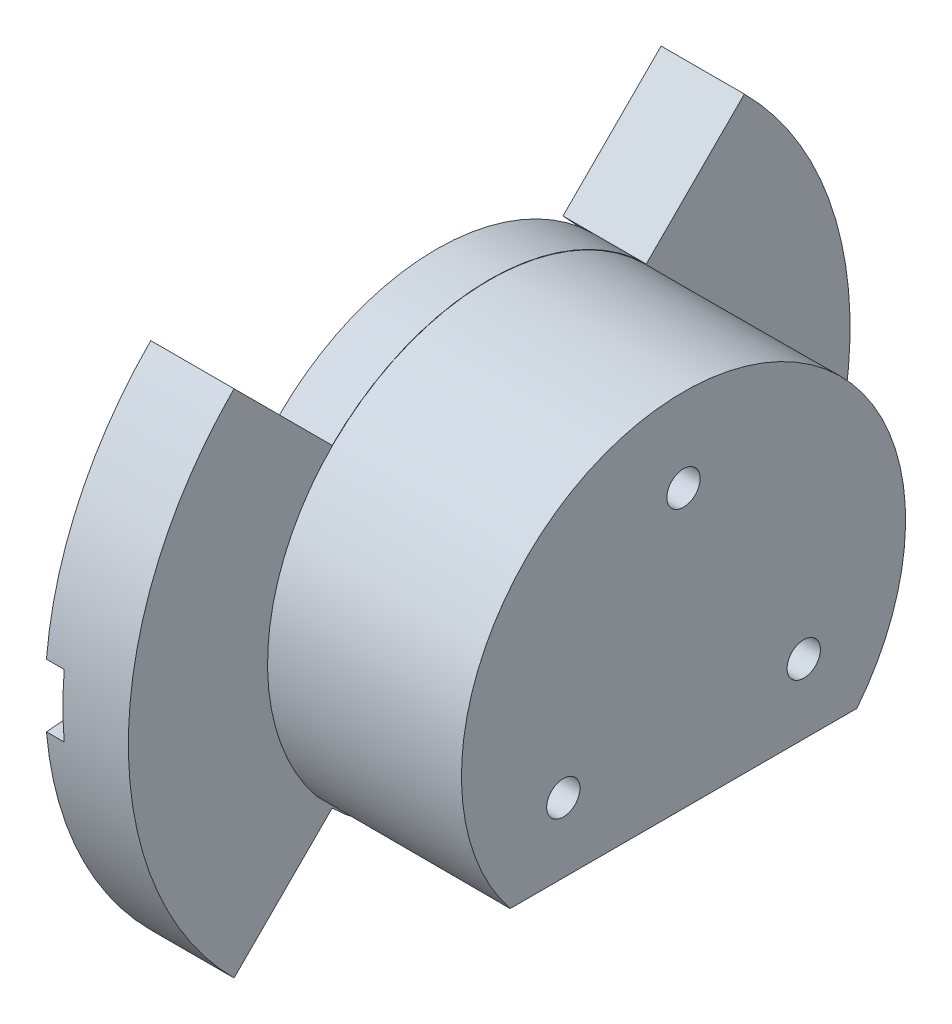
SolidWorks part; units mm, degrees
ref_plane "Alzado" through (0, 0, 0) normal (0, 0, 1) x (1, 0, 0)
ref_plane "Planta" through (0, 0, 0) normal (0, 1, 0) x (1, 0, 0)
ref_plane "Vista lateral" through (0, 0, 0) normal (1, 0, 0) x (0, 0, -1)
sketch "Croquis1" plane through (0, 0, 0) normal (0, 1, 0) x (1, 0, 0)
  line L0 (0, 0) -> (25, 0)
  line L1 (25, 0) -> (25, 20)
  line L2 (7.5, 19.9661) -> (25, 20)
  line L5 (7.5, 19.9661) -> (7.5, 32.5)
  line L6 (7.5, 32.5) -> (0, 32.5)
  line L7 (0, 32.5) -> (0, 20)
  line L8 (0, 20) -> (2.75, 20)
  line L9 (2.75, 20) -> (2.75, 10)
  line L10 (2.75, 10) -> (0, 10)
  line L11 (0, 10) -> (0, 0)
  dimension "D1" = 17.5
  dimension "D2" = 20
  dimension "D3" = 7.5
  dimension "D4" = 2.75
  dimension "D5" = 10
  dimension "D6" = 10
  dimension "D7" = 12.5
revolve "Revolución1" add sketch "Croquis1" angle 360 about L0
sketch "Croquis2" plane through (0, 0, 0) normal (-1, 0, 0) x (0, 0, 1)
  line L0 (0, 0) -> (22.981, 22.981)
  line L1 (-32.5, 0) -> (32.5, 0)
  line L2 (0, 0) -> (-22.981, 22.981)
  line L3 (0, 0) -> (22.981, -22.981)
  line L4 (0, 0) -> (-22.981, -22.981)
  circle A0 centre (0, 0) radius 32.5 construction
  circle A1 centre (0, 0) radius 20
  circle A2 centre (0, 0) radius 32.5
  dimension "D1" = 32.5
  dimension "D2" = 45
  dimension "D3" = 45
extrude "Cortar-Extruir2" cut sketch "Croquis2" against normal blind 7.5 contours L0 A2 L2 A1 | L4 A2 L3 A1
sketch "Croquis5" plane through (25, 0, 0) normal (1, 0, 0) x (0, 0, -1)
  circle A0 centre (0, 0) radius 12.5
  circle A1 centre (0, 12.5) radius 1.5
  circle A2 centre (10.8253, -6.25) radius 1.5
  circle A3 centre (-10.8253, -6.25) radius 1.5
  point P11 (0, 0)
  point P12 (0, 0)
  dimension "D1" = 3
  dimension "D2" = 25
  dimension "D3" = 3
extrude "Cortar-Extruir4" cut sketch "Croquis5" against normal blind 25 contours A0 A1 | A0 A1 | A0 A2 | A0 A2 | A0 A3 | A0 A3
sketch "Croquis17" plane through (0, 0, 0) normal (-1, 0, 0) x (0, 0, 1)
  line L0 (32.5, 0) -> (-32.5, 0)
  line L1 (0, 0) -> (32.3763, 2.8326)
  line L2 (0, 0) -> (32.3763, -2.8326)
  line L3 (0, 0) -> (-32.3763, -2.8326)
  line L4 (0, 0) -> (-32.3763, 2.8326)
  arc A0 (22.981, -22.981) -> (22.981, 22.981) centre (0, 0) ccw construction
  arc A1 (-22.981, 22.981) -> (-22.981, -22.981) centre (0, 0) ccw construction
  circle A2 centre (0, 0) radius 32.5
  circle A3 centre (0, 0) radius 26
  dimension "D3" = 52
  dimension "D1" = 5
  dimension "D2" = 5
extrude "Cortar-Extruir14" cut sketch "Croquis17" against normal blind 1.6 contours A3 L0 A2 L1 | A3 L2 A2 L0 | A3 L4 A2 L0 | A3 L0 A2 L3
sketch "Croquis18" plane through (0, 0, 0) normal (-1, 0, 0) x (0, 0, 1)
  line L0 (-1.86, 2.48) -> (1.86, 2.48)
  line L2 (0, 0) -> (1.86, 2.48)
  line L3 (0, 0) -> (-1.86, 2.48)
  circle A0 centre (0, 0) radius 3.1
  dimension "D1" = 6.2
  dimension "D2" = 73.74
extrude "Cortar-Extruir15" cut sketch "Croquis18" against normal blind 18 contours L3 A0 L2 | L3 L2 L0
sketch "Croquis20" plane through (25, 0, 0) normal (1, 0, 0) x (0, 0, -1)
  line L0 (0, 0) -> (0, -12.5)
  line L1 (-15.6125, -12.5) -> (15.6125, -12.5)
  circle A1 centre (0, 0) radius 20
  circle M4 centre (0, 0) radius 20
  dimension "D2" = 40
  dimension "D1" = 12.5
  dimension "D3" = 31.225
extrude "Cortar-Extruir18" cut sketch "Croquis20" against normal blind 17.5 contours L1 M4
sketch "Croquis21" plane through (0, -12.5, 0) normal (0, -1, 0) x (1, 0, 0)
  line L0 (0, 0) -> (16, 0)
  circle A0 centre (16, 0) radius 1
extrude "Cortar-Extruir19" cut sketch "Croquis21" against normal blind 12.5
sketch "Croquis22" plane through (0, 0, 0) normal (-1, 0, 0) x (0, 0, 1)
  circle A0 centre (0, 0) radius 12.5
  circle A1 centre (0, 12.5) radius 3.25
  circle A2 centre (10.8253, -6.25) radius 3.25
  circle A3 centre (-10.8253, -6.25) radius 3.25
  point P11 (0, 0)
  circle M2 centre (0, 0) radius 10
  dimension "D1" = 25
  dimension "D2" = 3
extrude "Cortar-Extruir20" cut sketch "Croquis22" against normal blind 5.5 contours A0 A1 | A0 A1 M2 | A0 A2 | A0 A2 M2 | A2 M2 | A1 M2 | A3 A0 M2 | A3 M2 | A0 A3
